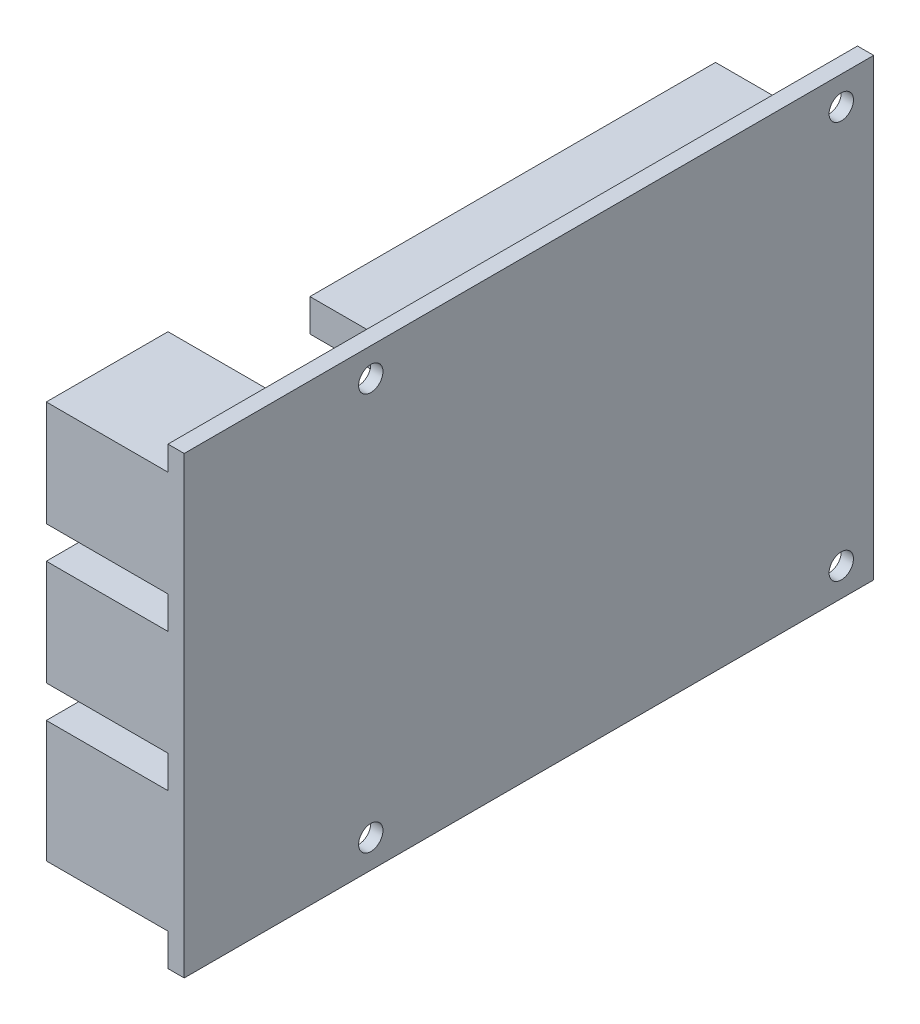
SolidWorks part; units mm, degrees
ref_plane "Plan de face" through (0, 0, 0) normal (0, 0, 1) x (1, 0, 0)
ref_plane "Plan de dessus" through (0, 0, 0) normal (0, 1, 0) x (1, 0, 0)
ref_plane "Plan de droite" through (0, 0, 0) normal (1, 0, 0) x (0, 0, -1)
sketch "Esquisse1" plane through (0, 0, 0) normal (1, 0, 0) x (0, 0, -1)
  line L1 (-42.5, -28) -> (42.5, -28)
  line L2 (-42.5, -28) -> (-42.5, 28)
  line L3 (-42.5, 28) -> (42.5, 28)
  line L4 (42.5, -28) -> (42.5, 28)
  line L5 (-42.5, -28) -> (42.5, 28) construction
  line L6 (-42.5, 28) -> (42.5, -28) construction
  point P0 (0, 0)
  dimension "D1" = 56
  dimension "D2" = 85
extrude "Boss.-Extru.1" add sketch "Esquisse1" along normal blind 2
sketch "Esquisse2" plane through (0, 0, 0) normal (-1, 0, 0) x (0, 0, 1)
  line L0 (42.5, 28) -> (42.5, -28) construction
  line L1 (42.5, -24) -> (22.5, -24)
  line L2 (42.5, -24) -> (42.5, -9)
  line L3 (42.5, -9) -> (22.5, -9)
  line L4 (22.5, -24) -> (22.5, -9)
  line L5 (-42.5, 28) -> (42.5, 28) construction
  line L6 (42.5, -5) -> (27.5, -5)
  line L7 (42.5, -5) -> (42.5, 8)
  line L8 (42.5, 8) -> (27.5, 8)
  line L9 (27.5, -5) -> (27.5, 8)
  line L10 (42.5, 12) -> (27.5, 12)
  line L11 (42.5, 12) -> (42.5, 25)
  line L12 (42.5, 25) -> (27.5, 25)
  line L13 (27.5, 12) -> (27.5, 25)
  dimension "D1" = 15
  dimension "D2" = 13
  dimension "D3" = 20
  dimension "D4" = 15
  dimension "D5" = 15
  dimension "D6" = 13
  dimension "D7" = 3
  dimension "D8" = 4
  dimension "D9" = 4
extrude "Boss.-Extru.2" add sketch "Esquisse2" along normal blind 15 contours L2 L1 L4 L3 | L7 L6 L9 L8 | L11 L10 L13 L12
sketch "Esquisse3" plane through (0, 0, 0) normal (-1, 0, 0) x (0, 0, 1)
  line L0 (-42.5, -28) -> (-42.5, 28) construction
  line L3 (42.5, 28) -> (42.5, 25) construction
  line L4 (-48.6726, 0) -> (45.7389, 0) construction
  circle A0 centre (-38.5, 24.5) radius 1.5
  circle A1 centre (19.5, 24.5) radius 1.5
  circle A6 centre (-38.5, -24.5) radius 1.5
  circle A7 centre (19.5, -24.5) radius 1.5
  dimension "D1" = 3
  dimension "D2" = 3
  dimension "D5" = 24.5
  dimension "D3" = 4
  dimension "D6" = 23
extrude "Enlèv. mat.-Extru.1" cut sketch "Esquisse3" against normal blind 15
sketch "Esquisse5" plane through (0, 0, 0) normal (-1, 0, 0) x (0, 0, 1)
  line L0 (-48.2559, 0) -> (62.0809, 0) construction
  circle A0 centre (19.5, 24.5) radius 2.5
  circle A1 centre (-38.5, 24.5) radius 2.5
  circle A2 centre (-38.5, -24.5) radius 2.5
  circle A3 centre (19.5, -24.5) radius 2.5
  dimension "D1" = 5
  dimension "D2" = 5
extrude "Enlèv. mat.-Extru.2" cut sketch "Esquisse5" against normal blind 0.5
sketch "Esquisse6" plane through (0, 0, 0) normal (-1, 0, 0) x (0, 0, 1)
  line L0 (-42.5, 28) -> (42.5, 28) construction
  line L1 (16, 22) -> (-34, 22)
  line L2 (16, 22) -> (16, 26)
  line L3 (16, 26) -> (-34, 26)
  line L4 (-34, 22) -> (-34, 26)
  circle A0 centre (19.5, 24.5) radius 2.5 construction
  point P4 (-34, 24)
  dimension "D2" = 3.5
  dimension "D1" = 50
  dimension "D3" = 4
  dimension "D4" = 2
extrude "Boss.-Extru.3" add sketch "Esquisse6" along normal blind 9
